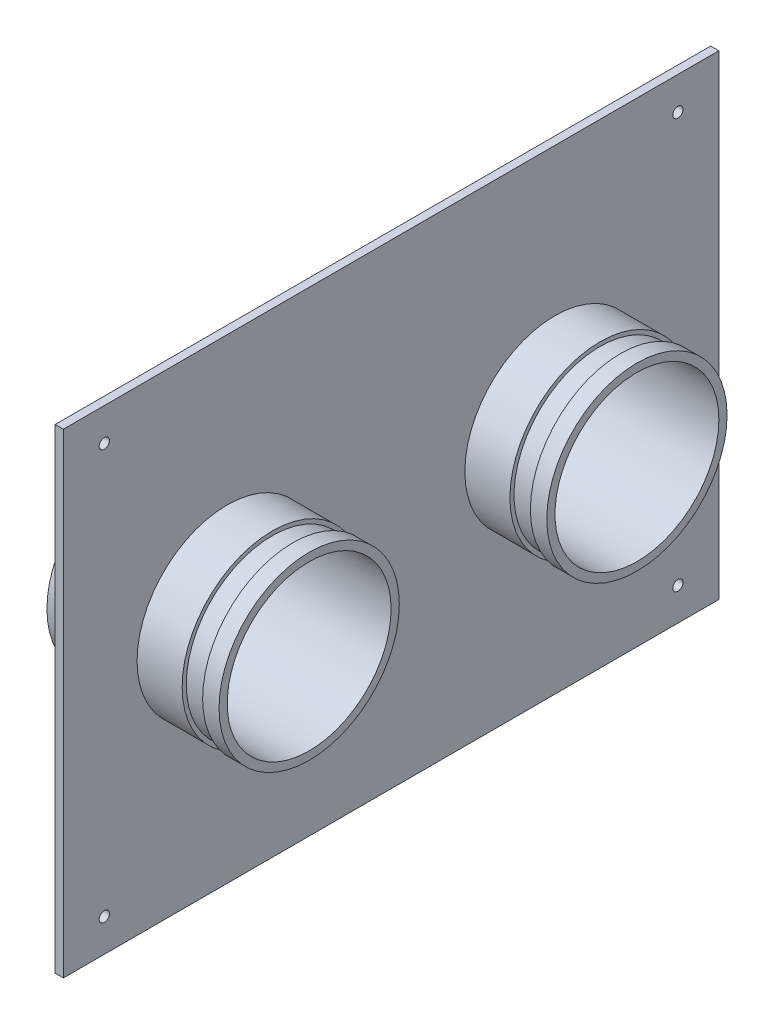
SolidWorks part; units mm, degrees
ref_plane "Front Plane" through (0, 0, 0) normal (0, 0, 1) x (1, 0, 0)
ref_plane "Top Plane" through (0, 0, 0) normal (0, 1, 0) x (1, 0, 0)
ref_plane "Right Plane" through (0, 0, 0) normal (1, 0, 0) x (0, 0, -1)
sketch "Sketch1" plane through (0, 0, 0) normal (1, 0, 0) x (0, 0, -1)
  line L0 (0, 0) -> (50.8, 0) construction
  line L1 (-101.6, 76.2) -> (101.6, 76.2)
  line L2 (-101.6, 76.2) -> (-101.6, -76.2)
  line L3 (-101.6, -76.2) -> (101.6, -76.2)
  line L4 (101.6, 76.2) -> (101.6, -76.2)
  line L5 (-101.6, 76.2) -> (101.6, -76.2) construction
  line L6 (-101.6, -76.2) -> (101.6, 76.2) construction
  line L7 (-50.8, 0) -> (0, 0) construction
  circle A0 centre (50.8, 0) radius 25.4
  circle A1 centre (-50.8, 0) radius 25.4
  point P0 (0, 0)
  dimension "D1" = 50.8
  dimension "D2" = 152.4
  dimension "D3" = 203.2
  dimension "D4" = 50.8
extrude "Boss-Extrude1" add sketch "Sketch1" along normal blind 2.54
sketch "Sketch2" plane through (2.54, 0, 0) normal (1, 0, 0) x (0, 0, -1)
  circle A0 centre (-50.8, 0) radius 27.94
  circle A1 centre (50.8, 0) radius 27.94
  circle A2 centre (-50.8, 0) radius 25.4 construction
  circle A3 centre (50.8, 0) radius 25.4 construction
  circle A4 centre (50.8, 0) radius 25.4
  circle A5 centre (-50.8, 0) radius 25.4
  dimension "D1" = 2.54
extrude "Boss-Extrude2" add sketch "Sketch2" along normal blind 25.4 and the other way blind 27.94
sketch "Sketch3" plane through (27.94, 0, 0) normal (1, 0, 0) x (0, 0, -1)
  circle A0 centre (50.8, 0) radius 26.67
  circle A1 centre (50.8, 0) radius 27.94 construction
  circle A2 centre (50.8, 0) radius 27.94 construction
  circle A3 centre (50.8, 0) radius 27.94
  dimension "D1" = 1.27
extrude "Cut-Extrude1" cut sketch "Sketch3" against normal blind 6.35 from offset 5.08 offset against normal yes
mirror "Mirror1" about plane through (0, 0, 0) normal (0, 0, 1) of "Cut-Extrude1"
sketch "Sketch4" plane through (2.54, 0, 0) normal (1, 0, 0) x (0, 0, -1)
  line L0 (88.9, 76.2) -> (88.9, -76.2) construction
  line L1 (101.6, 76.2) -> (-101.6, 76.2) construction
  line L2 (-101.6, -76.2) -> (101.6, -76.2) construction
  line L3 (101.6, -63.5) -> (-101.6, -63.5) construction
  line L4 (101.6, -76.2) -> (101.6, 76.2) construction
  line L5 (-101.6, 76.2) -> (-101.6, -76.2) construction
  line L6 (101.6, 63.5) -> (-101.6, 63.5) construction
  line L7 (-88.9, 76.2) -> (-88.9, -76.2) construction
  circle A0 centre (-88.9, 63.5) radius 1.5875
  circle A1 centre (88.9, 63.5) radius 1.5875
  circle A2 centre (88.9, -63.5) radius 1.5875
  circle A3 centre (-88.9, -63.5) radius 1.5875
  dimension "D1" = 3.175
  dimension "D2" = 12.7
  dimension "D3" = 12.7
  dimension "D4" = 12.7
  dimension "D5" = 12.7
extrude "Cut-Extrude2" cut sketch "Sketch4" against normal through all
sketch "Sketch5" plane through (2.54, 0, 0) normal (1, 0, 0) x (0, 0, -1)
  line L0 (101.6, -76.2) -> (101.6, 76.2) construction
  line L1 (-101.6, -76.2) -> (101.6, -76.2)
  line L2 (-101.6, -76.2) -> (-101.6, -73.66)
  line L3 (-101.6, -73.66) -> (101.6, -73.66)
  line L4 (101.6, -76.2) -> (101.6, -73.66)
  line L6 (-101.6, 76.2) -> (101.6, 76.2)
  line L7 (-101.6, 76.2) -> (-101.6, 73.66)
  line L8 (-101.6, 73.66) -> (101.6, 73.66)
  line L9 (101.6, 76.2) -> (101.6, 73.66)
  dimension "D1" = 2.54
extrude "Cut-Extrude3" cut sketch "Sketch5" against normal through all
